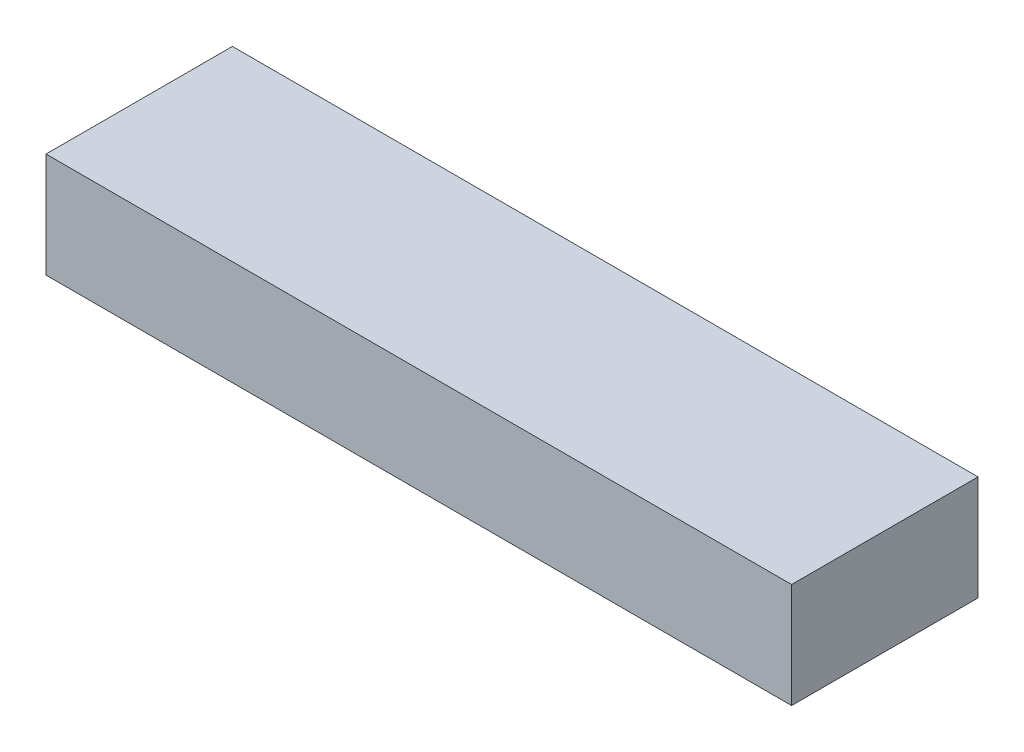
SolidWorks part; units mm, degrees
ref_plane "Front Plane" through (0, 0, 0) normal (0, 0, 1) x (1, 0, 0)
ref_plane "Top Plane" through (0, 0, 0) normal (0, 1, 0) x (1, 0, 0)
ref_plane "Right Plane" through (0, 0, 0) normal (1, 0, 0) x (0, 0, -1)
sketch "Sketch1" plane through (0, 0, 0) normal (0, 1, 0) x (1, 0, 0)
  line L1 (-101.6, 0) -> (0, 0)
  line L2 (-101.6, 0) -> (-101.6, -25.4)
  line L3 (-101.6, -25.4) -> (0, -25.4)
  line L4 (0, 0) -> (0, -25.4)
  dimension "D1" = 101.6
  dimension "D2" = 25.4
extrude "Boss-Extrude1" add sketch "Sketch1" along normal blind 14.2875
